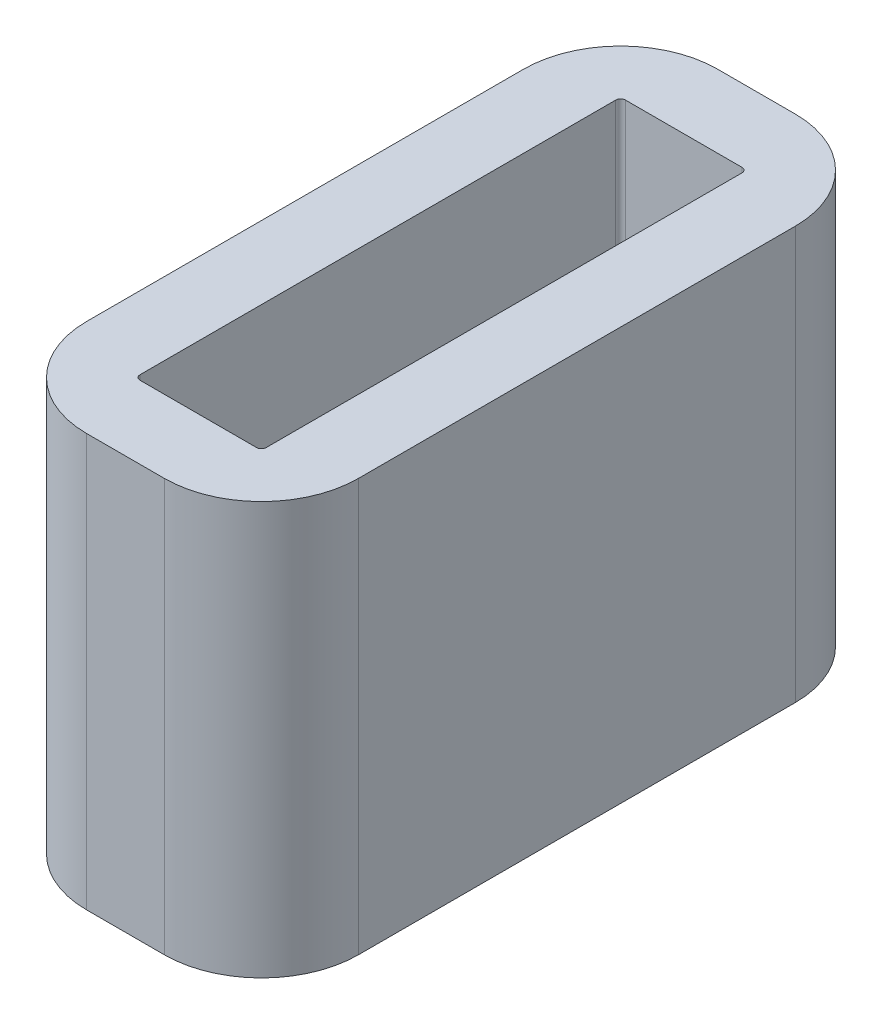
SolidWorks part; units mm, degrees
material "Copper"
ref_plane "Front Plane" through (0, 0, 0) normal (0, 0, 1) x (1, 0, 0)
ref_plane "Top Plane" through (0, 0, 0) normal (0, 1, 0) x (1, 0, 0)
ref_plane "Right Plane" through (0, 0, 0) normal (1, 0, 0) x (0, 0, -1)
sketch "Sketch1" plane through (0, 97.2795, 0) normal (0, 1, 0) x (1, 0, 0)
  line L0 (92.0978, 84.0094) -> (86.0478, 74.2094) construction
  line L1 (86.0478, 74.2094) -> (92.0978, 74.2094) construction
  line L2 (86.0478, 74.2094) -> (86.0478, 84.0094) construction
  line L3 (86.0478, 84.0094) -> (92.0978, 84.0094) construction
  line L4 (92.0978, 74.2094) -> (92.0978, 84.0094) construction
  line L6 (88.2728, 72.6094) -> (89.8728, 72.6094)
  line L7 (86.2728, 74.6094) -> (86.2728, 83.6094)
  line L8 (88.2728, 85.6094) -> (89.8728, 85.6094)
  line L9 (91.8728, 74.6094) -> (91.8728, 83.6094)
  line L10 (86.2728, 72.6094) -> (91.8728, 85.6094) construction
  line L11 (86.2728, 85.6094) -> (91.8728, 72.6094) construction
  line L12 (87.7728, 74.1094) -> (90.3728, 74.1094)
  line L13 (87.7728, 74.1094) -> (87.7728, 84.1094)
  line L14 (87.7728, 84.1094) -> (90.3728, 84.1094)
  line L15 (90.3728, 74.1094) -> (90.3728, 84.1094)
  line L16 (87.7728, 74.1094) -> (90.3728, 84.1094) construction
  line L17 (87.7728, 84.1094) -> (90.3728, 74.1094) construction
  arc A0 (88.2728, 72.6094) -> (86.2728, 74.6094) centre (88.2728, 74.6094) cw
  arc A1 (89.8728, 72.6094) -> (91.8728, 74.6094) centre (89.8728, 74.6094) ccw
  arc A2 (89.8728, 85.6094) -> (91.8728, 83.6094) centre (89.8728, 83.6094) cw
  arc A3 (86.2728, 83.6094) -> (88.2728, 85.6094) centre (88.2728, 83.6094) cw
  point P7 (89.0728, 79.1094)
  point P23 (89.0728, 79.1094)
  dimension "D3" = 2
  dimension "D1" = 5.6
  dimension "D2" = 13
  dimension "D4" = 2.6
  dimension "D5" = 10
extrude "Coil" add sketch "Sketch1" against normal blind 8.5 from offset 0.7 offset against normal yes
fillet "Fillet1" radius 0.1 4 edges at (90.3728, 92.3295, -74.1094) (87.7728, 92.3295, -74.1094) (87.7728, 92.3295, -84.1094) (90.3728, 92.3295, -84.1094)
